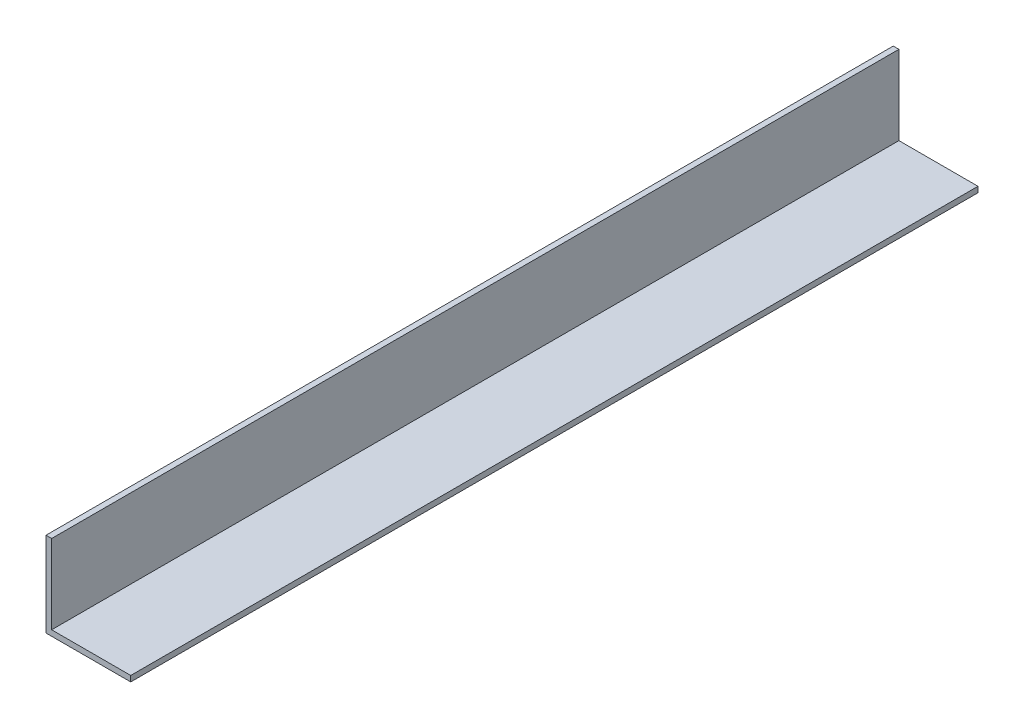
SolidWorks part; units mm, degrees
ref_plane "Front Plane" through (0, 0, 0) normal (0, 0, 1) x (1, 0, 0)
ref_plane "Top Plane" through (0, 0, 0) normal (0, 1, 0) x (1, 0, 0)
ref_plane "Right Plane" through (0, 0, 0) normal (1, 0, 0) x (0, 0, -1)
sketch "Sketch1" plane through (0, 0, 0) normal (0, 0, 1) x (1, 0, 0)
  line L0 (0, 0) -> (0, 30)
  line L1 (0, 30) -> (2, 30)
  line L2 (2, 30) -> (2, 2)
  line L3 (2, 2) -> (30, 2)
  line L4 (30, 2) -> (30, 0)
  line L5 (30, 0) -> (0, 0)
  dimension "D1" = 30
  dimension "D2" = 30
  dimension "D3" = 2
  dimension "D4" = 2
extrude "Boss-Extrude1" add sketch "Sketch1" against normal blind 300
